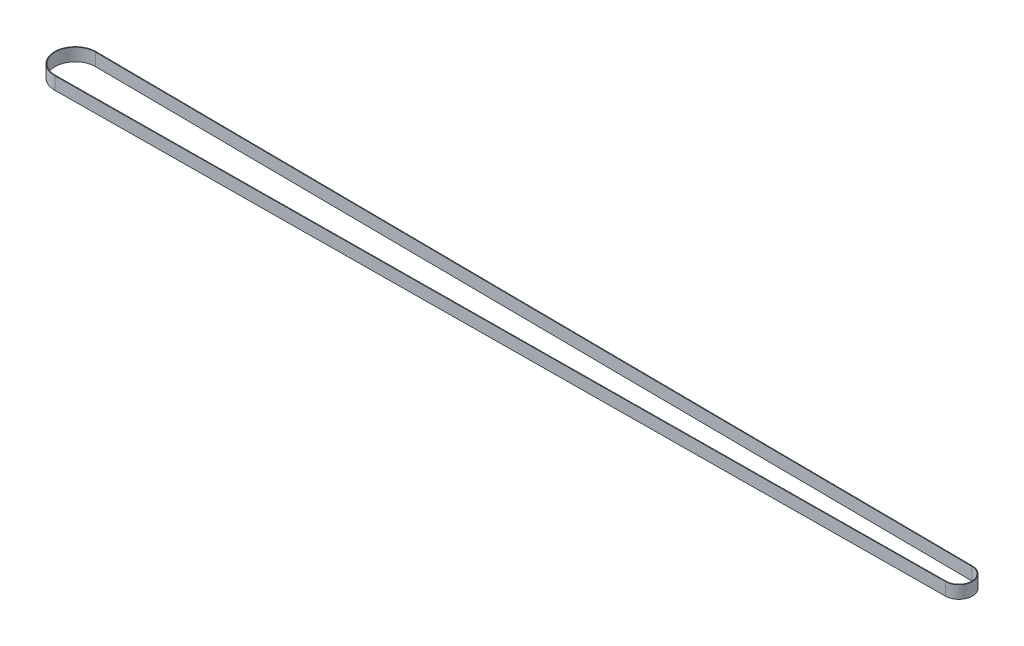
SolidWorks part; units mm, degrees
material "Rubber"
ref_plane "Front Plane" through (0, 0, 0) normal (0, 0, 1) x (1, 0, 0)
ref_plane "Top Plane" through (0, 0, 0) normal (0, 1, 0) x (1, 0, 0)
ref_plane "Right Plane" through (0, 0, 0) normal (1, 0, 0) x (0, 0, -1)
sketch "Sketch1" plane through (0, 0, 0) normal (0, 1, 0) x (1, 0, 0)
  line L0 (-222.1278, 0) -> (196.9722, 0) construction
  line L1 (196.9722, -6.096) -> (-221.9719, -9.5237)
  line L2 (-221.9719, -9.5237) -> (-221.9296, -9.5313)
  line L3 (-221.9667, -9.8387) -> (196.9722, -6.411)
  line L4 (196.9722, 6.096) -> (-221.9719, 9.5237)
  line L5 (-221.9719, 9.5237) -> (-221.944, 9.5216)
  line L6 (-221.9667, 9.8387) -> (196.9722, 6.411)
  arc A0 (-221.9719, 9.5237) -> (-221.9719, -9.5237) centre (-222.1278, 0) ccw
  arc A1 (196.9722, -6.096) -> (196.9722, 6.096) centre (196.9722, 0) ccw
  arc A2 (-221.9667, 9.8387) -> (-221.9667, -9.8387) centre (-222.1278, 0) ccw
  arc A3 (196.9722, -6.411) -> (196.9722, 6.411) centre (196.9722, 0) ccw
  dimension "D1" = 419.1
  dimension "D2" = 19.05
  dimension "D3" = 12.192
  dimension "D4" = 19.68
  dimension "D5" = 12.822
extrude "Boss-Extrude1" add sketch "Sketch1" along normal blind 6
